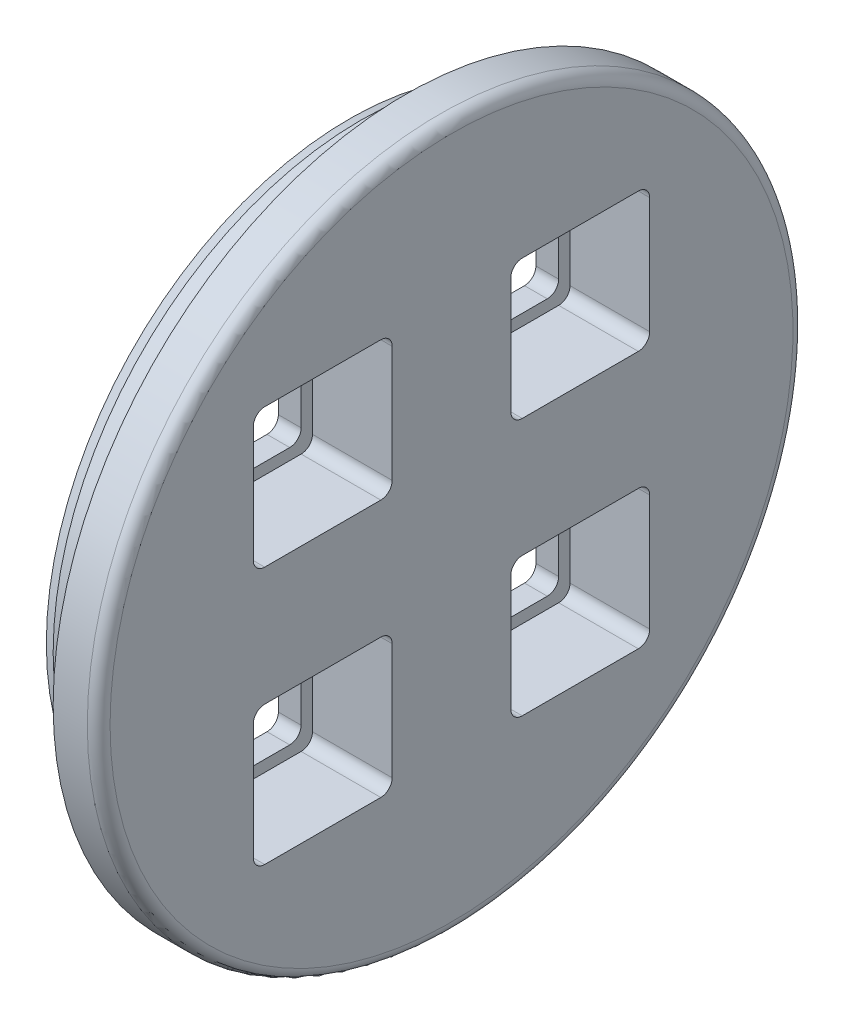
SolidWorks part; units mm, degrees
ref_plane "Front" through (0, 0, 0) normal (0, 0, 1) x (1, 0, 0)
ref_plane "Top" through (0, 0, 0) normal (0, 1, 0) x (1, 0, 0)
ref_plane "Right" through (0, 0, 0) normal (1, 0, 0) x (0, 0, -1)
sketch "Çizim1" plane through (0, 0, 0) normal (0, 0, 1) x (1, 0, 0)
  line L0 (0, 0) -> (45, 0) construction
  line L1 (48.1633, 0) -> (48.1633, 55.2041) construction
  line L2 (0, 0) -> (0, 55.2041) construction
  line L3 (0, 31) -> (5, 31)
  line L4 (0, 31) -> (0, 133)
  line L5 (5, 135) -> (25, 135)
  line L6 (25, 31) -> (25, 16)
  line L7 (25, 16) -> (35, 16)
  line L8 (45, 0) -> (45, 148.5)
  line L10 (40, 155) -> (25, 155)
  line L11 (25, 155) -> (25, 135)
  line L12 (7.3, 31) -> (25, 31)
  line L13 (5, 32.75) -> (7.3, 32.75)
  line L14 (5, 32.75) -> (5, 31)
  line L16 (7.3, 32.75) -> (7.3, 31)
  line L17 (0, 133) -> (5, 135)
  line L18 (35, 16) -> (35, 0)
  line L19 (35, 0) -> (45, 0)
  line L20 (45, 148.5) -> (45, 150)
  arc A0 (40, 155) -> (45, 150) centre (40, 150) cw
  point P8 (0, 135)
  point P24 (45, 155)
  dimension "D15" = 5
  dimension "D1" = 31
  dimension "D2" = 25
  dimension "D3" = 135
  dimension "D4" = 20
  dimension "D5" = 32
  dimension "D6" = 20
  dimension "D7" = 155
  dimension "D8" = 5
  dimension "D9" = 2.3
  dimension "D10" = 32.75
  dimension "D11" = 5
  dimension "D12" = 2
  dimension "D13" = 10
  dimension "D14" = 6.5
revolve "Döndür1" add sketch "Çizim1" angle 360 about L0
sketch "Sketch2" plane through (0, 0, 0) normal (-1, 0, 0) x (0, 0, 1)
  line L0 (0, 0) -> (-56.5685, 56.5685) construction
  line L1 (82.0685, 87.0685) -> (31.0685, 87.0685)
  line L6 (-82.0685, 87.0685) -> (-31.0685, 87.0685)
  line L7 (-87.0685, 82.0685) -> (-87.0685, 31.0685)
  line L8 (-82.0685, 26.0685) -> (-31.0685, 26.0685)
  line L9 (-26.0685, 82.0685) -> (-26.0685, 31.0685)
  line L10 (-87.0685, 87.0685) -> (-26.0685, 26.0685) construction
  line L11 (-87.0685, 26.0685) -> (-26.0685, 87.0685) construction
  line L12 (87.0685, 82.0685) -> (87.0685, 31.0685)
  line L13 (82.0685, 26.0685) -> (31.0685, 26.0685)
  line L14 (26.0685, 82.0685) -> (26.0685, 31.0685)
  line L15 (87.0685, -82.0685) -> (87.0685, -31.0685)
  line L16 (82.0685, -87.0685) -> (31.0685, -87.0685)
  line L17 (26.0685, -82.0685) -> (26.0685, -31.0685)
  line L18 (82.0685, -26.0685) -> (31.0685, -26.0685)
  line L19 (-82.0685, -87.0685) -> (-31.0685, -87.0685)
  line L20 (-87.0685, -82.0685) -> (-87.0685, -31.0685)
  line L21 (-82.0685, -26.0685) -> (-31.0685, -26.0685)
  line L22 (-26.0685, -82.0685) -> (-26.0685, -31.0685)
  arc A4 (-87.0685, 31.0685) -> (-82.0685, 26.0685) centre (-82.0685, 31.0685) ccw
  arc A5 (-31.0685, 26.0685) -> (-26.0685, 31.0685) centre (-31.0685, 31.0685) ccw
  arc A6 (-31.0685, 87.0685) -> (-26.0685, 82.0685) centre (-31.0685, 82.0685) cw
  arc A7 (-82.0685, 87.0685) -> (-87.0685, 82.0685) centre (-82.0685, 82.0685) ccw
  arc A8 (87.0685, 82.0685) -> (82.0685, 87.0685) centre (82.0685, 82.0685) ccw
  arc A9 (31.0685, 87.0685) -> (26.0685, 82.0685) centre (31.0685, 82.0685) ccw
  arc A10 (87.0685, 31.0685) -> (82.0685, 26.0685) centre (82.0685, 31.0685) cw
  arc A11 (26.0685, 31.0685) -> (31.0685, 26.0685) centre (31.0685, 31.0685) ccw
  arc A12 (82.0685, -87.0685) -> (87.0685, -82.0685) centre (82.0685, -82.0685) ccw
  arc A13 (87.0685, -31.0685) -> (82.0685, -26.0685) centre (82.0685, -31.0685) ccw
  arc A14 (31.0685, -87.0685) -> (26.0685, -82.0685) centre (31.0685, -82.0685) cw
  arc A15 (31.0685, -26.0685) -> (26.0685, -31.0685) centre (31.0685, -31.0685) ccw
  arc A16 (-87.0685, -82.0685) -> (-82.0685, -87.0685) centre (-82.0685, -82.0685) ccw
  arc A17 (-31.0685, -87.0685) -> (-26.0685, -82.0685) centre (-31.0685, -82.0685) ccw
  arc A18 (-87.0685, -31.0685) -> (-82.0685, -26.0685) centre (-82.0685, -31.0685) cw
  arc A19 (-26.0685, -31.0685) -> (-31.0685, -26.0685) centre (-31.0685, -31.0685) ccw
  point P58 (0, 0)
  point P61 (0, 0)
  dimension "D3" = 61
  dimension "D4" = 5
  dimension "D1" = 80
  dimension "D2" = 61
  dimension "D5" = 4
extrude "Cut-Extrude1" cut sketch "Sketch2" against normal through all from offset 10 offset against normal yes
sketch "Sketch4" plane through (0, 0, 0) normal (-1, 0, 0) x (0, 0, 1)
  line L0 (0, 0) -> (56.5685, -56.5685) construction
  line L1 (0, 0) -> (-56.5685, -56.5685) construction
  line L2 (36.0685, -31.0685) -> (77.0685, -31.0685)
  line L3 (31.0685, -36.0685) -> (31.0685, -77.0685)
  line L4 (36.0685, -82.0685) -> (77.0685, -82.0685)
  line L5 (82.0685, -36.0685) -> (82.0685, -77.0685)
  line L6 (31.0685, -31.0685) -> (82.0685, -82.0685) construction
  line L7 (31.0685, -82.0685) -> (82.0685, -31.0685) construction
  line L8 (-36.0685, -31.0685) -> (-77.0685, -31.0685)
  line L9 (-31.0685, -36.0685) -> (-31.0685, -77.0685)
  line L10 (-36.0685, -82.0685) -> (-77.0685, -82.0685)
  line L11 (-82.0685, -36.0685) -> (-82.0685, -77.0685)
  line L12 (0, 0) -> (-56.5685, 56.5685) construction
  line L13 (-31.0685, 36.0685) -> (-31.0685, 77.0685)
  line L14 (-36.0685, 31.0685) -> (-77.0685, 31.0685)
  line L15 (-82.0685, 36.0685) -> (-82.0685, 77.0685)
  line L16 (-36.0685, 82.0685) -> (-77.0685, 82.0685)
  line L17 (0, 0) -> (56.5685, 56.5685) construction
  line L18 (36.0685, 31.0685) -> (77.0685, 31.0685)
  line L19 (31.0685, 36.0685) -> (31.0685, 77.0685)
  line L20 (36.0685, 82.0685) -> (77.0685, 82.0685)
  line L21 (82.0685, 36.0685) -> (82.0685, 77.0685)
  arc A0 (36.0685, -31.0685) -> (31.0685, -36.0685) centre (36.0685, -36.0685) ccw
  arc A1 (31.0685, -77.0685) -> (36.0685, -82.0685) centre (36.0685, -77.0685) ccw
  arc A2 (77.0685, -82.0685) -> (82.0685, -77.0685) centre (77.0685, -77.0685) ccw
  arc A3 (77.0685, -31.0685) -> (82.0685, -36.0685) centre (77.0685, -36.0685) cw
  arc A4 (-77.0685, -31.0685) -> (-82.0685, -36.0685) centre (-77.0685, -36.0685) ccw
  arc A5 (-31.0685, -36.0685) -> (-36.0685, -31.0685) centre (-36.0685, -36.0685) ccw
  arc A6 (-31.0685, -77.0685) -> (-36.0685, -82.0685) centre (-36.0685, -77.0685) cw
  arc A7 (-82.0685, -77.0685) -> (-77.0685, -82.0685) centre (-77.0685, -77.0685) ccw
  arc A8 (-31.0685, 77.0685) -> (-36.0685, 82.0685) centre (-36.0685, 77.0685) ccw
  arc A9 (-36.0685, 31.0685) -> (-31.0685, 36.0685) centre (-36.0685, 36.0685) ccw
  arc A10 (-77.0685, 31.0685) -> (-82.0685, 36.0685) centre (-77.0685, 36.0685) cw
  arc A11 (-77.0685, 82.0685) -> (-82.0685, 77.0685) centre (-77.0685, 77.0685) ccw
  arc A12 (77.0685, 31.0685) -> (82.0685, 36.0685) centre (77.0685, 36.0685) ccw
  arc A13 (31.0685, 36.0685) -> (36.0685, 31.0685) centre (36.0685, 36.0685) ccw
  arc A14 (31.0685, 77.0685) -> (36.0685, 82.0685) centre (36.0685, 77.0685) cw
  arc A15 (82.0685, 77.0685) -> (77.0685, 82.0685) centre (77.0685, 77.0685) ccw
  point P61 (0, 0)
  dimension "D4" = 5
  dimension "D1" = 80
  dimension "D2" = 51
  dimension "D3" = 51
  dimension "D5" = 4
extrude "Cut-Extrude2" cut sketch "Sketch4" against normal through all
